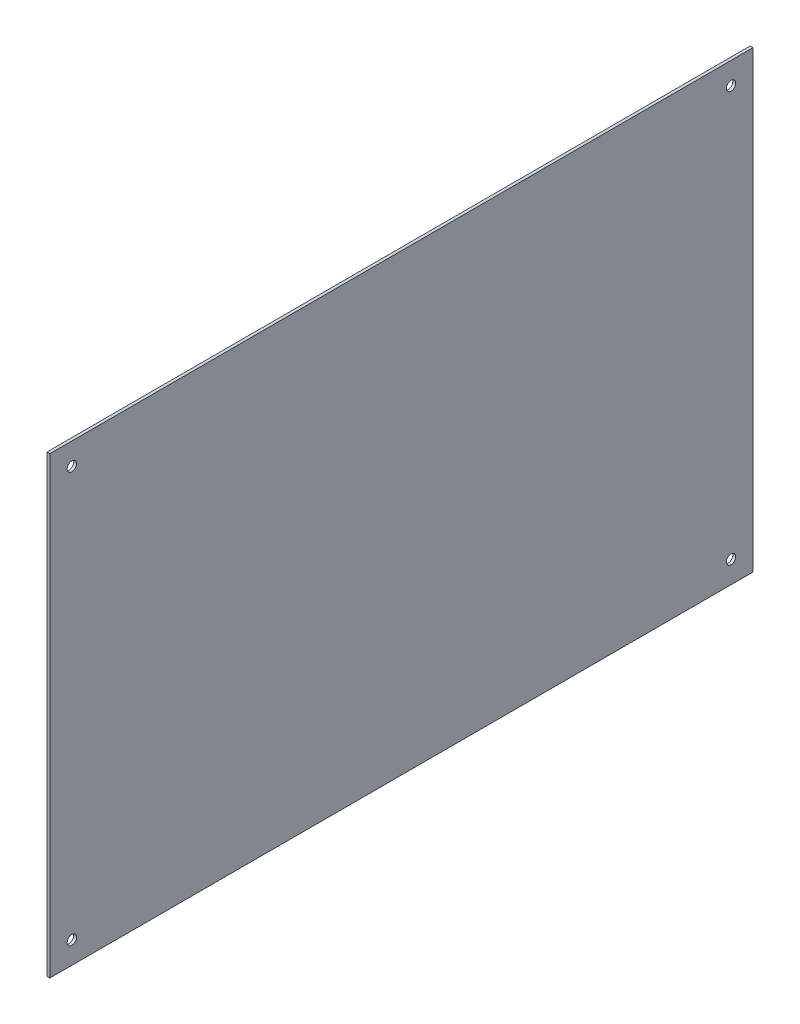
SolidWorks part; units mm, degrees
ref_plane "Front" through (0, 0, 0) normal (0, 0, 1) x (1, 0, 0)
ref_plane "Top" through (0, 0, 0) normal (0, 1, 0) x (1, 0, 0)
ref_plane "Right" through (0, 0, 0) normal (1, 0, 0) x (0, 0, -1)
sketch "ｽｹｯﾁ2" plane through (0, 0, 0) normal (1, 0, 0) x (0, 0, -1)
  line L1 (-120, -77.5) -> (120, -77.5)
  line L2 (-120, -77.5) -> (-120, 77.5)
  line L3 (-120, 77.5) -> (120, 77.5)
  line L4 (120, -77.5) -> (120, 77.5)
  line L5 (0, 77.5) -> (0, -77.5) construction
  line L6 (-120, 0) -> (120, 0) construction
  circle A0 centre (-112.5, 70) radius 1.6
  circle A1 centre (-112.5, -70) radius 1.6
  circle A2 centre (112.5, -70) radius 1.6
  circle A3 centre (112.5, 70) radius 1.6
  point P0 (0, 0)
  dimension "D3" = 3.2
  dimension "D4" = 3.2
  dimension "D5" = 3.2
  dimension "D6" = 3.2
  dimension "D7" = 7.5
  dimension "D8" = 7.5
  dimension "D9" = 7.5
  dimension "D10" = 7.5
  dimension "D11" = 7.5
  dimension "D12" = 7.5
  dimension "D13" = 7.5
  dimension "D14" = 7.5
  dimension "D1" = 240
  dimension "D2" = 155
extrude "ﾎﾞｽ - 押し出し1" add sketch "ｽｹｯﾁ2" along normal blind 1
